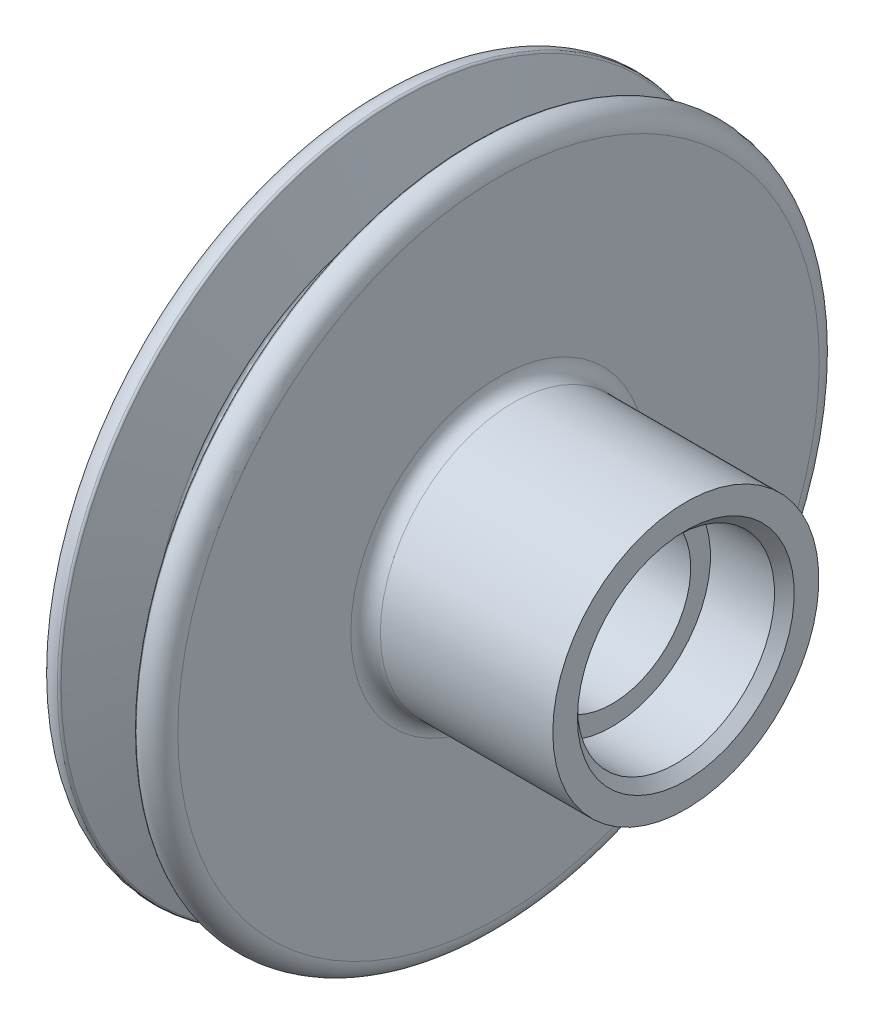
SolidWorks part; units mm, degrees
ref_plane "Piano frontale" through (0, 0, 0) normal (0, 0, 1) x (1, 0, 0)
ref_plane "Piano superiore" through (0, 0, 0) normal (0, 1, 0) x (1, 0, 0)
ref_plane "Piano destro" through (0, 0, 0) normal (1, 0, 0) x (0, 0, -1)
sketch "Schizzo1" plane through (0, 0, 0) normal (0, 0, 1) x (1, 0, 0)
  line L2 (4.8185, 69) -> (9.4044, 54)
  line L3 (9.4044, 54) -> (15.5956, 54)
  line L4 (15.5956, 54) -> (20.1815, 69)
  line L6 (25, 65.0846) -> (25, 27)
  line L7 (25, 27) -> (63, 27)
  line L8 (63, 27) -> (63, 20)
  line L9 (63, 20) -> (48, 20)
  line L10 (48, 20) -> (48, 16)
  line L11 (48, 16) -> (18, 16)
  line L12 (18, 16) -> (18, 20)
  line L13 (18, 20) -> (0, 20)
  line L14 (-22.8662, 0) -> (111.6358, 0) construction
  line L15 (12.5, 76.6737) -> (12.5, 54) construction
  line L16 (-2.0528, 63.5) -> (27.0528, 63.5) construction
  line L17 (0, 20) -> (0, 31)
  line L18 (0, 31) -> (8, 31)
  line L20 (8, 37) -> (0, 37)
  line L21 (0, 37) -> (0, 65.0846)
  arc A0 (0, 65.0846) -> (4.8185, 69) centre (4, 65.0846) cw
  arc A1 (20.1815, 69) -> (25, 65.0846) centre (21, 65.0846) cw
  arc A3 (8, 37) -> (8, 31) centre (8, 34) cw
  point P4 (12.5, 63.5)
  point P7 (12.5, 54)
  point P24 (18.5, 63.5)
  point P28 (11, 34)
  point P33 (6.5, 63.5)
  dimension "D1" = 9.5
  dimension "D5" = 4
  dimension "D6" = 5.5
  dimension "D2" = 25
  dimension "D3" = 12.5
  dimension "D4" = 34
  dimension "D7" = 62
  dimension "D8" = 108
  dimension "D9" = 12
  dimension "D10" = 54
  dimension "D11" = 40
  dimension "D12" = 32
  dimension "D13" = 40
  dimension "D14" = 74
  dimension "D15" = 11
  dimension "D16" = 63
  dimension "D17" = 18
  dimension "D18" = 30
revolve "Rivoluzione1" add sketch "Schizzo1" angle 360 about L14
fillet "Raccordo1" radius 0.5 2 edges at (20.1815, 0, 69) (4.8185, 0, 69)
fillet "Raccordo2" radius 1 2 edges at (15.5956, 0, 54) (9.4044, 0, 54)
fillet "Raccordo3" radius 3 1 edges at (25, 0, 27)
chamfer "Smusso1" distance 2 2 edges at (0, 0, 20) (63, 0, 20)
